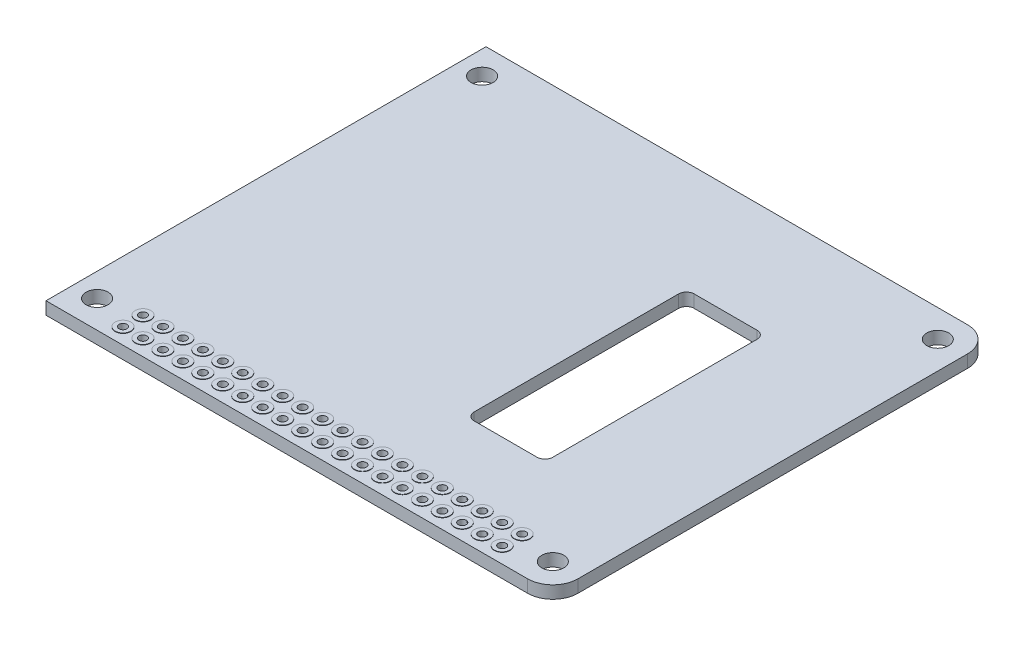
SolidWorks part; units mm, degrees
material "A-Glass Fiber"
ref_plane "Front" through (0, 0, 0) normal (0, 0, 1) x (1, 0, 0)
ref_plane "Top" through (0, 0, 0) normal (0, 1, 0) x (1, 0, 0)
ref_plane "Right" through (0, 0, 0) normal (1, 0, 0) x (0, 0, -1)
sketch "Sketch1" plane through (0, 0, 0) normal (0, 1, 0) x (1, 0, 0)
  line L0 (0, 0) -> (32.25, 0) construction
  line L1 (-32.25, -28) -> (29.05, -28)
  line L2 (-32.25, -28) -> (-32.25, 28)
  line L3 (-32.25, 28) -> (29.05, 28)
  line L4 (32.25, -24.8) -> (32.25, 24.8)
  line L5 (-32.25, -28) -> (32.25, 28) construction
  line L6 (-32.25, 28) -> (32.25, -28) construction
  line L8 (16.25, -14) -> (8.25, -14)
  line L9 (17.25, -13) -> (17.25, 13)
  line L10 (16.25, 14) -> (8.25, 14)
  line L11 (7.25, -13) -> (7.25, 13)
  line L12 (17.25, -14) -> (7.25, 14) construction
  line L13 (17.25, 14) -> (7.25, -14) construction
  arc A0 (29.05, -28) -> (32.25, -24.8) centre (29.05, -24.8) ccw
  arc A1 (29.05, 28) -> (32.25, 24.8) centre (29.05, 24.8) cw
  circle A2 centre (-29.25, -24.5) radius 1.4
  circle A3 centre (-29.25, 24.5) radius 1.4
  circle A4 centre (28.75, 24.5) radius 1.4
  circle A5 centre (28.75, -24.5) radius 1.4
  arc A6 (16.25, -14) -> (17.25, -13) centre (16.25, -13) ccw
  arc A7 (8.25, -14) -> (7.25, -13) centre (8.25, -13) cw
  arc A8 (17.25, 13) -> (16.25, 14) centre (16.25, 13) ccw
  arc A9 (8.25, 14) -> (7.25, 13) centre (8.25, 13) ccw
  point P0 (0, 0)
  point P22 (12.25, 0)
  dimension "D3" = 3.2
  dimension "D5" = 3.5
  dimension "D6" = 2.8
  dimension "D7" = 3.5
  dimension "D8" = 49
  dimension "D10" = 2.8
  dimension "D11" = 2.8
  dimension "D12" = 58
  dimension "D14" = 3.5
  dimension "D15" = 3.5
  dimension "D19" = 1
  dimension "D4" = 58
  dimension "D9" = 49
  dimension "D1" = 56
  dimension "D2" = 64.5
  dimension "D16" = 39.5
  dimension "D17" = 49.5
  dimension "D18" = 14
extrude "Boss-Extrude1" add sketch "Sketch1" along normal blind 1.6
sketch "Sketch2" plane through (0, 1.6, 0) normal (0, 1, 0) x (1, 0, 0)
  line L0 (-32.25, 28) -> (-32.25, -28) construction
  line L1 (-32.25, -28) -> (29.05, -28) construction
  circle A0 centre (-24.45, -26) radius 0.5
  dimension "D1" = 1
  dimension "D2" = 7.8
  dimension "D3" = 2
extrude "Cut-Extrude1" cut sketch "Sketch2" against normal through all
sketch "Sketch3" plane through (0, 1.6, 0) normal (0, 1, 0) x (1, 0, 0)
  circle A0 centre (-24.45, -26) radius 1
  circle A1 centre (-24.45, -26) radius 0.5
  dimension "D1" = 2
extrude "Boss-Extrude2" add sketch "Sketch3" along normal blind 0.05
pattern_linear "LPattern1" count 20 spacing 2.54 along (1, 0, 0) count 2 spacing 2.54 along (0, 0, -1) of "Cut-Extrude1", "Boss-Extrude2"
sketch "Sketch4" plane through (0, 0, 0) normal (0, -1, 0) x (1, 0, 0)
  line L0 (7.25, 0) -> (-32.25, 0) construction
  line L1 (7.25, -13) -> (7.25, 13) construction
  line L2 (-32.25, -28) -> (-32.25, 28) construction
  line L4 (-5.25, -12.5) -> (-6.25, -12.5)
  line L5 (-5.25, -12.5) -> (-5.25, 12.5)
  line L6 (-5.25, 12.5) -> (-6.25, 12.5)
  line L7 (-6.25, -12.5) -> (-6.25, 12.5)
  line L8 (-5.25, -12.5) -> (-6.25, 12.5) construction
  line L9 (-5.25, 12.5) -> (-6.25, -12.5) construction
  point P6 (-5.75, 0)
  dimension "D1" = 1
  dimension "D2" = 27
  dimension "D3" = 25
extrude "Boss-Extrude3" add sketch "Sketch4" along normal blind 1
